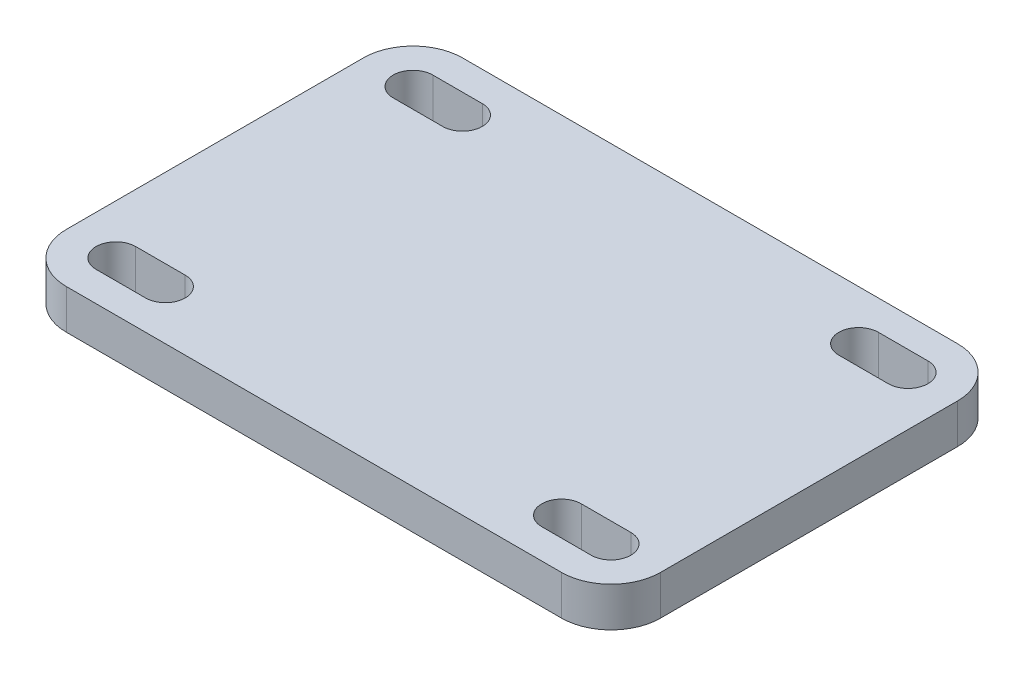
SolidWorks part; units mm, degrees
ref_plane "Front Plane" through (0, 0, 0) normal (0, 0, 1) x (1, 0, 0)
ref_plane "Top Plane" through (0, 0, 0) normal (0, 1, 0) x (1, 0, 0)
ref_plane "Right Plane" through (0, 0, 0) normal (1, 0, 0) x (0, 0, -1)
sketch "Sketch1" plane through (0, 0, 0) normal (0, 1, 0) x (1, 0, 0)
  line L1 (25, -20) -> (-25, -20)
  line L2 (30, -15) -> (30, 15)
  line L3 (25, 20) -> (-25, 20)
  line L4 (-30, -15) -> (-30, 15)
  line L5 (30, -20) -> (-30, 20) construction
  line L6 (30, 20) -> (-30, -20) construction
  arc A0 (-25, -20) -> (-30, -15) centre (-25, -15) cw
  arc A1 (25, -20) -> (30, -15) centre (25, -15) ccw
  arc A2 (30, 15) -> (25, 20) centre (25, 15) ccw
  arc A3 (-25, 20) -> (-30, 15) centre (-25, 15) ccw
  point P0 (0, 0)
  dimension "D3" = 5
  dimension "D1" = 60
  dimension "D2" = 40
extrude "Boss-Extrude1" add sketch "Sketch1" along normal blind 4
sketch "Sketch2" plane through (0, 4, 0) normal (0, 1, 0) x (1, 0, 0)
  line L0 (-25, 15) -> (-20, 15) construction
  line L1 (-25, 17) -> (-20, 17)
  line L2 (-25, 13) -> (-20, 13)
  line L3 (0, -55) -> (0, 55) construction
  line L4 (25, 15) -> (20, 15) construction
  line L5 (25, 17) -> (20, 17)
  line L6 (25, 13) -> (20, 13)
  line L7 (-55, 0) -> (55, 0) construction
  line L8 (25, -15) -> (20, -15) construction
  line L9 (25, -17) -> (20, -17)
  line L10 (25, -13) -> (20, -13)
  line L11 (-25, -15) -> (-20, -15) construction
  line L12 (-25, -17) -> (-20, -17)
  line L13 (-25, -13) -> (-20, -13)
  arc A0 (-25, 17) -> (-25, 13) centre (-25, 15) ccw
  arc A1 (-20, 13) -> (-20, 17) centre (-20, 15) ccw
  arc A2 (25, 17) -> (25, 13) centre (25, 15) cw
  arc A3 (20, 13) -> (20, 17) centre (20, 15) cw
  arc A4 (25, -17) -> (25, -13) centre (25, -15) ccw
  arc A5 (20, -13) -> (20, -17) centre (20, -15) ccw
  arc A6 (-25, -17) -> (-25, -13) centre (-25, -15) cw
  arc A7 (-20, -13) -> (-20, -17) centre (-20, -15) cw
  point P2 (-22.5, 15)
  point P12 (22.5, 15)
  point P21 (22.5, -15)
  point P28 (-22.5, -15)
  dimension "D1" = 2
  dimension "D2" = 5
  dimension "D3" = 22.5
  dimension "D4" = 15
extrude "Cut-Extrude1" cut sketch "Sketch2" against normal blind 4
